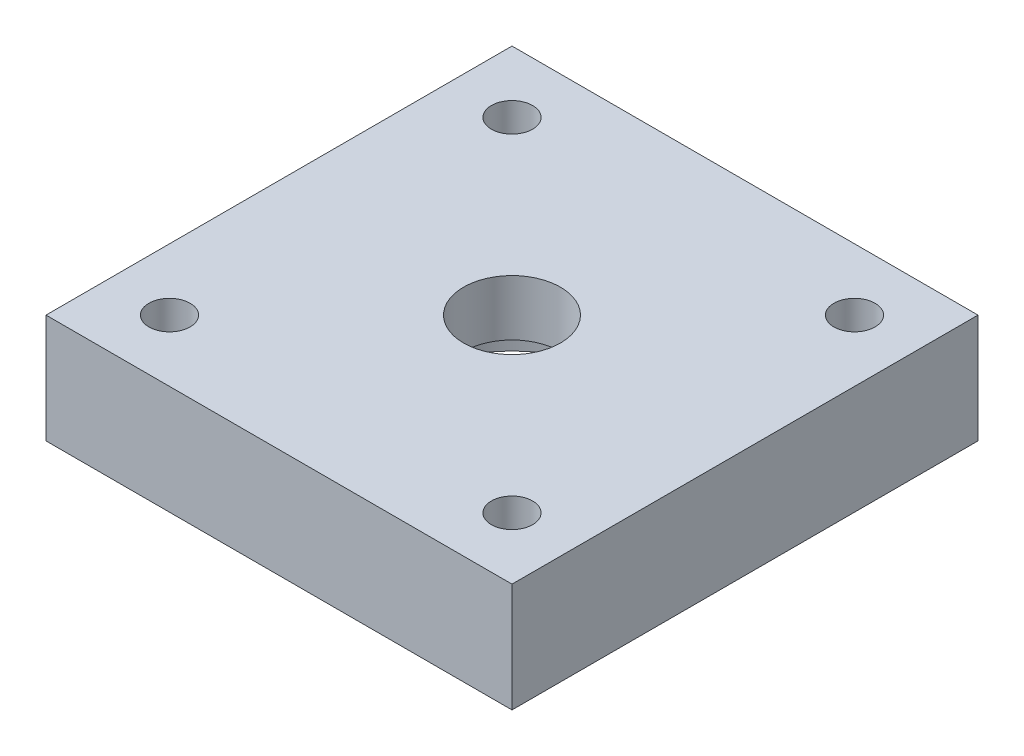
SolidWorks part; units mm, degrees
material "1060 Alloy"
ref_plane "Front" through (0, 0, 0) normal (0, 0, 1) x (1, 0, 0)
ref_plane "Top" through (0, 0, 0) normal (0, 1, 0) x (1, 0, 0)
ref_plane "Right" through (0, 0, 0) normal (1, 0, 0) x (0, 0, -1)
sketch "Sketch1" plane through (0, 0, 0) normal (0, 1, 0) x (1, 0, 0)
  line L1 (-48.1053, 48.1053) -> (48.1053, 48.1053)
  line L2 (-48.1053, 48.1053) -> (-48.1053, -48.1053)
  line L3 (-48.1053, -48.1053) -> (48.1053, -48.1053)
  line L4 (48.1053, 48.1053) -> (48.1053, -48.1053)
  line L5 (-48.1053, 48.1053) -> (48.1053, -48.1053) construction
  line L6 (-48.1053, -48.1053) -> (48.1053, 48.1053) construction
  circle A0 centre (-35.3553, 35.3553) radius 4.25
  circle A1 centre (35.3553, 35.3553) radius 4.25
  circle A2 centre (35.3553, -35.3553) radius 4.25
  circle A3 centre (-35.3553, -35.3553) radius 4.25
  point P0 (0, 0)
  point P17 (0, 0)
  dimension "D3" = 8.5
  dimension "D2" = 50
  dimension "D5" = 50
  dimension "D6" = 50
  dimension "D1" = 12.75
  dimension "D7" = 96.2107
  dimension "D4" = 4
extrude "body extrusion and bolt holes" add sketch "Sketch1" along normal blind 22.5
sketch "Sketch2" plane through (0, 0, 0) normal (0, 0, 1) x (1, 0, 0)
  line L0 (0, 0) -> (0, 14.5)
  line L1 (-48.1053, 0) -> (48.1053, 0) construction
  line L2 (0, 14.5) -> (22.725, 6.5)
  line L3 (22.725, 6.5) -> (22.725, 0)
  line L4 (22.725, 0) -> (0, 0)
  dimension "D1" = 22.725
  dimension "D2" = 14.5
  dimension "D3" = 6.5
revolve "main chamber" cut sketch "Sketch2" angle 360 about L0
sketch "Sketch3" plane through (0, 22.5, 0) normal (0, 1, 0) x (1, 0, 0)
  circle A0 centre (0, 0) radius 10
  dimension "D1" = 20
extrude "entrance" cut sketch "Sketch3" against normal blind 22.5
sketch "Sketch5" plane through (0, 0, 0) normal (1, 0, 0) x (0, 0, -1)
  line L0 (-22.725, 6.5) -> (22.725, 6.5) construction
  line L1 (-22.725, 6.5) -> (-22.725, 0) construction
  circle A0 centre (-20.225, 4) radius 2.5
  dimension "D1" = 5
extrude "Cut-Extrude1" cut sketch "Sketch5" against normal blind 100
equation "\"motor mount pattern diameter\"= 30mm"
equation "\"D2@Sketch1\" = \"motor mount to housing m8 pattern diameter\" / 2"
equation "\"D3@Sketch1\" = \"motor mount to housing m8 screw hole diameter\""
equation "\"D5@Sketch1\" = \"motor mount to housing m8 pattern diameter\" / 2"
equation "\"D6@Sketch1\" = \"motor mount to housing m8 pattern diameter\" / 2"
equation "\"D1@Sketch1\" = \"motor mount to housing m8 screw post radius\""
equation "\"D1@body extrusion and bolt holes\" = \"housing top total thickness\""
equation "\"D1@Sketch2\" = \"housing top impeller cavity diameter\" / 2"
equation "\"D2@Sketch2\" = \"housing top impeller cavity height\""
equation "\"D3@Sketch2\" = \"housing top impeller cavity tip height\""
equation "\"D1@Sketch3\" = \"housing top entrance OD\""
equation "\"D1@entrance\" = \"housing top total thickness\""
equation "\"bearing OD\" = 20mm"
equation "\"bearing outer race thickness\"= 1mm"
equation "\"bearing ID\"= 10mm"
equation "\"bearing depth\"= 6mm"
equation "\"bearing inner race thickness\"= 1mm"
equation "\"seal OD\" = 20mm"
equation "\"seal ID\"= 8mm"
equation "\"seal depth\"= 6mm"
equation "\"impeller base outer diameter\"= 1.75in"
equation "\"impeller base outer thickness\"= 1mm"
equation "\"impeller base center thickness\"= 5mm"
equation "\"impeller number of vanes\"= 8"
equation "\"impeller vane inner height\"= 8mm"
equation "\"impeller primary vane opening diamater\"= 10mm"
equation "\"impeller vane inner thickness\"= .75mm"
equation "\"impeller vane outer thickness\"= 1.5mm"
equation "\"impeller primary vane entrance angle\"= 20deg"
equation "\"impeller secondary vane entrance angle\"= 20deg"
equation "\"impeller secondary vane opening diameter\"= 10mm"
equation "\"motor to housing distance\"= 60mm"
equation "\"motor mount coupler shaft hole diameter\"= \"coupler shaft base diameter\"+ 4mm"
equation "\"motor mount to housing m8 screw hole diameter\"= 8.5mm"
equation "\"motor mount to housing m8 screw post radius\"= ( 3 * \"motor mount to housing m8 screw hole diameter\" ) / 2"
equation "\"motor mount to housing m8 pattern diameter\"= 100mm"
equation "\"motor mount to housing m4 screw hole diamater\"= 4mm"
equation "\"motor mount to housing m4 head diameter\"= 7.25mm"
equation "\"motor mount to housing m4 head depth\"= 4mm"
equation "\"motor mount plate thickness\"= 6mm + \"motor mount to housing m4 head depth\""
equation "\"housing bearing seat lip thickness\" = 2mm"
equation "\"housing base thickness\"= \"housing bearing seat lip thickness\" + \"seal depth\" + \"bearing depth\""
equation "\"housing top impeller vertical clearance\"= .5mm"
equation "\"housing top impeller horizontal clearance\"= .5mm"
equation "\"housing top impeller bottom clearance\"= 1mm"
equation "\"housing top impeller cavity height\"= \"housing top impeller bottom clearance\" + \"impeller base center thickness\" + \"impeller vane inner height\" + \"housing top impeller vertical clearance\""
equation "\"housing top impeller cavity diameter\"= 2 * \"housing top impeller horizontal clearance\" + \"impeller base outer diameter\""
equation "\"housing top impeller cavity tip height\"= \"housing top impeller bottom clearance\" + \"housing top impeller vertical clearance\" + \"impeller base outer thickness\" + \"impeller vane outer height\""
equation "\"housing top entrance OD\"= 20mm"
equation "\"housing top exit OD\"= 5mm"
equation "\"housing top o-ring channel height\"= 1.5mm"
equation "\"housing top o ring channel width\"= 1.5mm"
equation "\"housing top threaded inlet depth\"= 8mm"
equation "\"housing top total thickness\"= \"housing top threaded inlet depth\" + \"housing top impeller cavity height\""
equation "\"housing top total width\"= 10mm"
equation "\"housing top exit threaded diameter\"= 8mm"
equation "\"housing top exit threaded depth\"= 8mm"
equation "\"motor shaft pride\"= 32mm"
equation "\"motor shaft flat section length from tip\"= 25.7mm"
equation "\"motor shaft bore end clearance\"= 2mm"
equation "\"motor mount shaft hole depth\"= \"motor shaft pride\""
equation "\"coupler shaft set screw drill hole diameter\"= 6mm"
equation "\"coupler shaft set screw 1 distance\"= \"motor mount shaft hole depth\" / 3"
equation "\"coupler shaft set screw 2 distance\"= \"motor mount shaft hole depth\" * 4 / 5"
equation "\"coupler shaft motor shaft hole diameter\"= 8mm"
equation "\"coupler shaft base diameter\"= 18mm"
equation "\"coupler shaft base length\"= \"motor mount shaft hole depth\" + 10mm"
equation "\"coupler shaft second section diameter\"= \"bearing ID\" + \"bearing inner race thickness\" * 2"
equation "\"coupler shaft second section length\"= \"motor to housing distance\" -  \"coupler shaft base length\" - 2mm"
equation "\"coupler shaft third section diamater\"= \"bearing ID\""
equation "\"coupler shaft third section length\"= \"bearing depth\""
equation "\"coupler shaft seal section diameter\" = \"seal ID\""
equation "\"coupler shaft seal section length\" = \"housing base thickness\"+\"housing top impeller bottom clearance\"-\"bearing depth\""
equation "\"coupler shaft impeller section diameter\" = 6mm"
equation "\"coupler shaft impeller section length\" = \"impeller boss depth\"+\"impeller base center thickness\" - 1mm"
equation "\"coupler shaft impeller screw hole diameter\" = \"motor mount to housing m4 screw hole diamater\""
equation "\"coupler shaft impeller screw hole depth\" = 10mm"
equation "\"housing top o-ring circumference\" = 250mm"
equation "\"housing top o-ring radius\" = (\"housing top o-ring circumference\")/(2*3.14)"
equation "\"impeller vane outer height\"= 4mm"
equation "\"impeller bolt surface height\" = 5mm"
equation "\"impeller bolt surface diameter\" = 8mm"
equation "\"impeller boss depth\" = 5mm"
equation "\"impeller dowel diameter\" = 2mm"
equation "\"coupler shaft to motor clearance\" = 2mm"
equation "\"impeller boss diameter\" = \"coupler shaft impeller section diameter\"+2*5mm"
equation "\"impeller dowel length\" = 2mm*2 + \"coupler shaft impeller section diameter\""
equation "\"D1@Sketch5\"=\"housing top exit OD\" "
